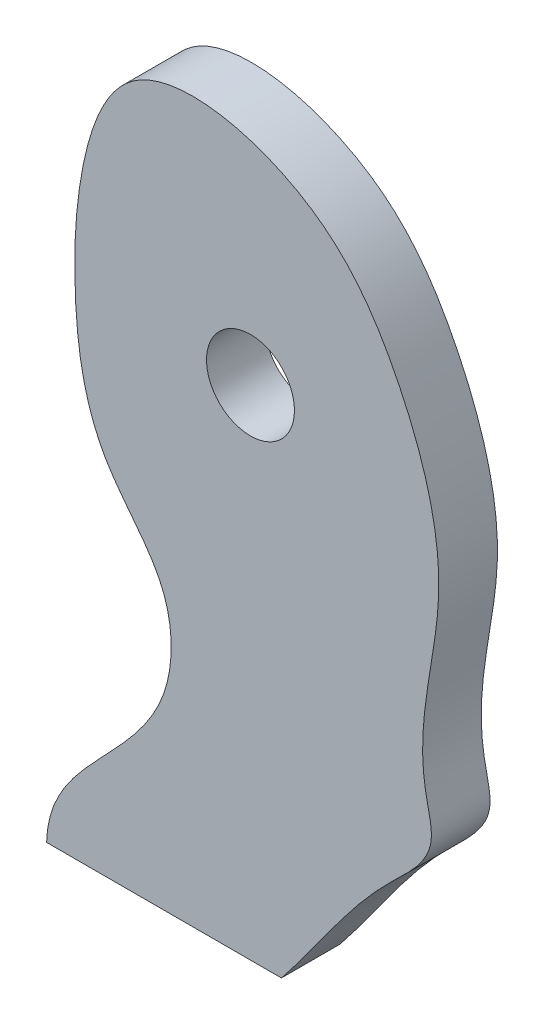
SolidWorks part; units mm, degrees
ref_plane "Front Plane" through (0, 0, 0) normal (0, 0, 1) x (1, 0, 0)
ref_plane "Top Plane" through (0, 0, 0) normal (0, 1, 0) x (1, 0, 0)
ref_plane "Right Plane" through (0, 0, 0) normal (1, 0, 0) x (0, 0, -1)
sketch "Sketch1" plane through (0, 0, 0) normal (0, 0, 1) x (1, 0, 0)
  line L0 (106.6667, 215) -> (533.3333, 215) construction
  line L1 (118.9671, 34.1672) -> (131.679, 34.1672)
  circle A0 centre (130.0027, 61.1275) radius 2.3813
  spline S0 degree 3 poles (118.9671, 34.1672) (119.0303, 36.647) (121.9064, 39.5447) (125.7936, 43.7986) (125.8915, 49.657) (121.1275, 53.8813) (120.3675, 60.3341) (120.6007, 66.4839) (123.017, 74.7228) (133.6485, 72.2218) (138.4936, 65.1338) (141.3382, 56.3814) (138.5876, 49.4279) (140.2627, 43.9947) (135.7141, 40.1856) (133.7297, 36.7142) (131.679, 34.1672) knots 0 0 0 0 0.071905 0.130595 0.180106 0.241275 0.322804 0.375401 0.447915 0.55529 0.628867 0.728218 0.835004 0.857708 0.898521 1 1 1 1
  dimension "D32" = 4.7625
  dimension "D1" = 118.9671
  dimension "D2" = 119.945
  dimension "D3" = 120.5037
  dimension "D4" = 120.7831
  dimension "D5" = 122.18
  dimension "D6" = 123.5769
  dimension "D7" = 125.323
  dimension "D8" = 131.679
  dimension "D9" = 133.495
  dimension "D10" = 133.7743
  dimension "D11" = 137.546
  dimension "D12" = 137.8254
  dimension "D13" = 139.5017
  dimension "D14" = 139.781
  dimension "D15" = 140.2001
  dimension "D16" = 34.1672
  dimension "D17" = 36.961
  dimension "D18" = 37.2404
  dimension "D19" = 39.8945
  dimension "D20" = 41.5708
  dimension "D21" = 44.3646
  dimension "D22" = 44.644
  dimension "D23" = 46.7394
  dimension "D24" = 48.9744
  dimension "D25" = 53.7239
  dimension "D26" = 56.6574
  dimension "D27" = 61.1275
  dimension "D28" = 65.5976
  dimension "D29" = 66.0167
  dimension "D30" = 70.9059
  dimension "D31" = 72.1631
extrude "Boss-Extrude1" add sketch "Sketch1" along normal blind 3.175
